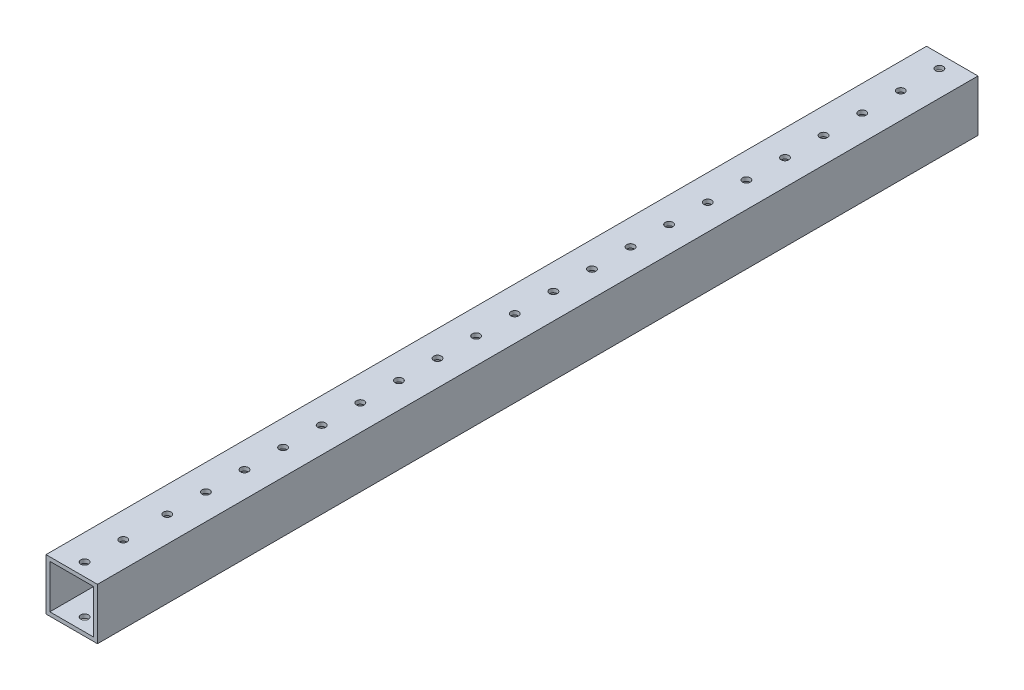
SolidWorks part; units mm, degrees
material "6061 合金"
ref_plane "前视基准面" through (0, 0, 0) normal (0, 0, 1) x (1, 0, 0)
ref_plane "上视基准面" through (0, 0, 0) normal (0, 1, 0) x (1, 0, 0)
ref_plane "右视基准面" through (0, 0, 0) normal (1, 0, 0) x (0, 0, -1)
other "Configuration Table"
sketch "草图1" plane through (0, 0, 0) normal (0, 0, 1) x (1, 0, 0)
  line L1 (-8.5, 8.5) -> (8.5, 8.5)
  line L2 (-8.5, 8.5) -> (-8.5, -8.5)
  line L3 (-8.5, -8.5) -> (8.5, -8.5)
  line L4 (8.5, 8.5) -> (8.5, -8.5)
  line L5 (-8.5, 8.5) -> (8.5, -8.5) construction
  line L6 (-8.5, -8.5) -> (8.5, 8.5) construction
  line L7 (-10, 10) -> (10, 10)
  line L8 (-10, 10) -> (-10, -10)
  line L9 (-10, -10) -> (10, -10)
  line L10 (10, 10) -> (10, -10)
  line L11 (-10, 10) -> (10, -10) construction
  line L12 (-10, -10) -> (10, 10) construction
  point P0 (0, 0)
  point P6 (0, 0)
  dimension "D1" = 20
  dimension "D2" = 20
  dimension "D3" = 1.5
  dimension "D4" = 1.5
extrude "凸台-拉伸1" add sketch "草图1" along normal blind 342.12
sketch "草图2" plane through (0, 10, 0) normal (0, 1, 0) x (1, 0, 0)
  line L0 (0, 0) -> (0, -50000) construction
  line L1 (10, 0) -> (-10, 0) construction
  line L2 (10, -342.12) -> (-10, -342.12) construction
  circle A0 centre (0, -5) radius 1.5
  circle A1 centre (0, -20) radius 1.5
  circle A2 centre (0, -337.12) radius 1.5
  circle A3 centre (0, -322.12) radius 1.5
  dimension "D1" = 5
  dimension "D2" = 15
  dimension "D3" = 3
  dimension "D4" = 5
  dimension "D5" = 15
extrude "切除-拉伸1" cut sketch "草图2" against normal through all
sketch "草图3" plane through (0, 10, 0) normal (0, 1, 0) x (1, 0, 0)
  line L0 (0, 0) -> (0, -50000) construction
  line L1 (0, -35) -> (0, -50) construction
  circle A0 centre (0, -35) radius 1.5
  circle A1 centre (0, -50) radius 1.5
  circle A2 centre (0, -65) radius 1.5
  circle A3 centre (0, -80) radius 1.5
  circle A4 centre (0, -95) radius 1.5
  circle A5 centre (0, -110) radius 1.5
  circle A6 centre (0, -125) radius 1.5
  circle A7 centre (0, -140) radius 1.5
  circle A8 centre (0, -155) radius 1.5
  circle A9 centre (0, -170) radius 1.5
  circle A10 centre (0, -185) radius 1.5
  circle A11 centre (0, -200) radius 1.5
  circle A12 centre (0, -215) radius 1.5
  circle A13 centre (0, -230) radius 1.5
  circle A14 centre (0, -245) radius 1.5
  circle A15 centre (0, -260) radius 1.5
  circle A16 centre (0, -275) radius 1.5
  circle A17 centre (0, -290) radius 1.5
  circle A18 centre (0, -305) radius 1.5
  circle A19 centre (0, -20) radius 1.5 construction
  dimension "D3" = 3
  dimension "D4" = 15
  dimension "D2" = 15
  dimension "D1" = 19
extrude "切除-拉伸2" cut sketch "草图3" against normal through all
sketch "草图4" [suppressed] plane through (-10, 0, 0) normal (-1, 0, 0) x (0, 0, 1)
  line L0 (235.04, 0) -> (-49764.96, 0) construction
  line L1 (265.04, 10) -> (265.04, -10) construction
  circle A0 centre (222.54, 0) radius 1.6
  circle A1 centre (242.54, 0) radius 1.6
  point P11 (265.04, 0)
  dimension "D1" = 3.2
  dimension "D2" = 20
  dimension "D3" = 22.5
extrude "切除-拉伸3" [suppressed] cut sketch "草图4" against normal through all
sketch "草图5" [suppressed] plane through (0, -10, 0) normal (0, -1, 0) x (1, 0, 0)
  line L0 (0, 0) -> (0, -50000) construction
  line L1 (-10, 0) -> (10, 0) construction
  line L2 (0, 10) -> (0, 30) construction
  circle A0 centre (0, 10) radius 1.6
  circle A1 centre (0, 30) radius 1.6
  circle A2 centre (0, 50) radius 1.6
  circle A3 centre (0, 70) radius 1.6
  circle A4 centre (0, 90) radius 1.6
  circle A5 centre (0, 110) radius 1.6
  circle A6 centre (0, 130) radius 1.6
  circle A7 centre (0, 150) radius 1.6
  circle A8 centre (0, 170) radius 1.6
  circle A9 centre (0, 190) radius 1.6
  circle A10 centre (0, 210) radius 1.6
  circle A11 centre (0, 230) radius 1.6
  dimension "D1" = 10
  dimension "D2" = 3.2
  dimension "D4" = 20
  dimension "D3" = 12
extrude "切除-拉伸4" [suppressed] cut sketch "草图5" against normal through all
sketch "草图6" [suppressed] plane through (0, 10, 0) normal (0, 1, 0) x (1, 0, 0)
  line L0 (0, 0) -> (0, -50000) construction
  line L1 (10, 0) -> (-10, 0) construction
  line L2 (0, -10) -> (0, -30) construction
  circle A0 centre (0, -10) radius 1.5
  circle A1 centre (0, -30) radius 1.5
  circle A2 centre (0, -50) radius 1.5
  circle A3 centre (0, -70) radius 1.5
  circle A4 centre (0, -90) radius 1.5
  circle A5 centre (0, -110) radius 1.5
  circle A6 centre (0, -130) radius 1.5
  circle A7 centre (0, -150) radius 1.5
  dimension "D1" = 3
  dimension "D2" = 10
  dimension "D4" = 20
  dimension "D3" = 8
extrude "切除-拉伸5" [suppressed] cut sketch "草图6" against normal through all
